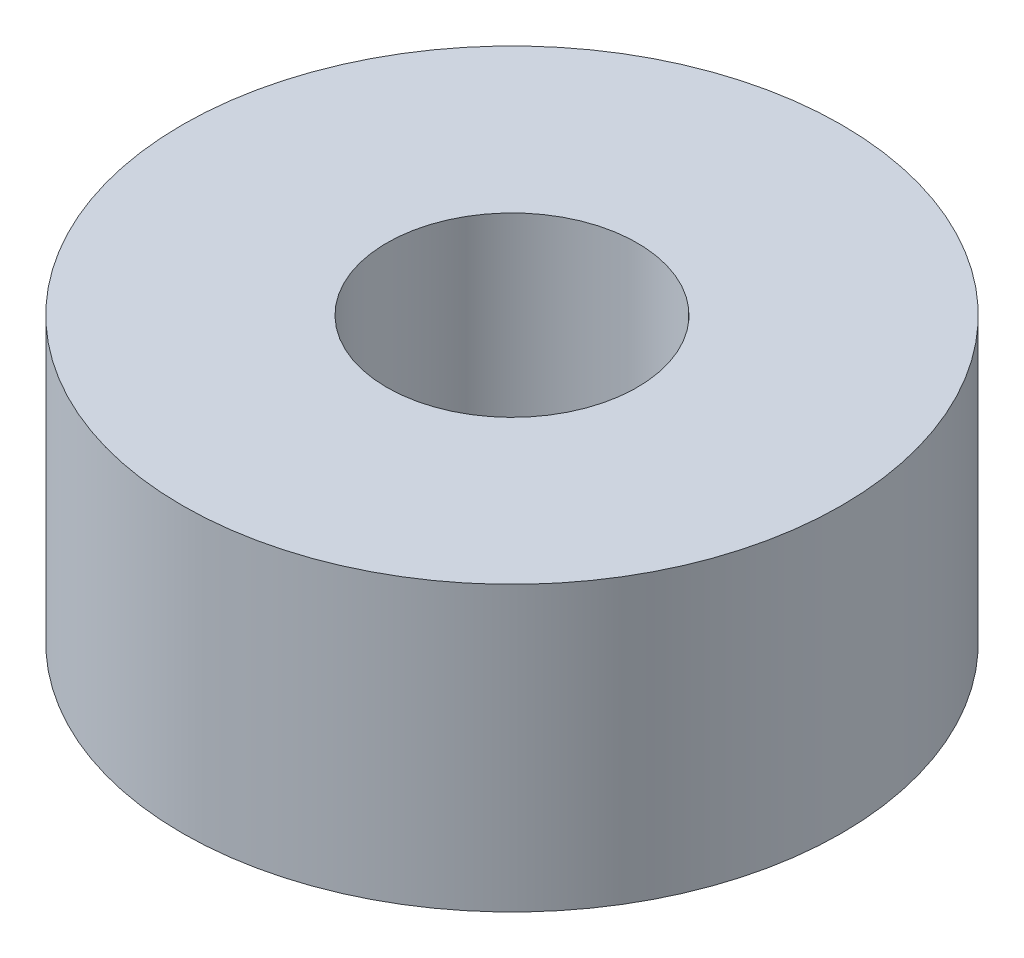
SolidWorks part; units mm, degrees
ref_plane "前视基准面" through (0, 0, 0) normal (0, 0, 1) x (1, 0, 0)
ref_plane "上视基准面" through (0, 0, 0) normal (0, 1, 0) x (1, 0, 0)
ref_plane "右视基准面" through (0, 0, 0) normal (1, 0, 0) x (0, 0, -1)
sketch "草图1" plane through (0, 0, 0) normal (0, 1, 0) x (1, 0, 0)
  circle A0 centre (0, 0) radius 1.5
  circle A1 centre (0, 0) radius 3.95
  dimension "D1" = 3
  dimension "D2" = 7.9
extrude "凸台-拉伸1" add sketch "草图1" along normal blind 3.4
